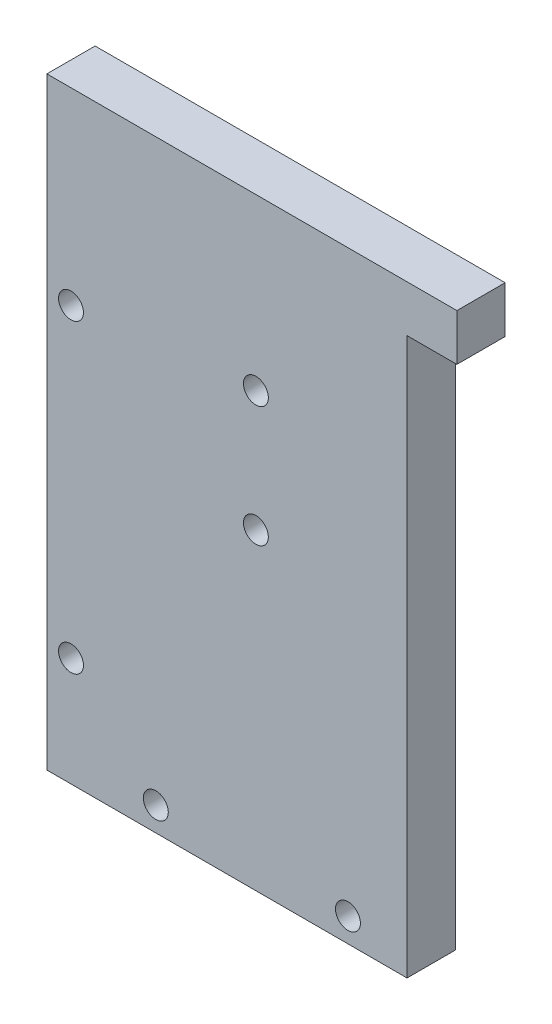
SolidWorks part; units mm, degrees
ref_plane "Płaszczyzna przednia" through (0, 0, 0) normal (0, 0, 1) x (1, 0, 0)
ref_plane "Płaszczyzna górna" through (0, 0, 0) normal (0, 1, 0) x (1, 0, 0)
ref_plane "Płaszczyzna prawa" through (0, 0, 0) normal (1, 0, 0) x (0, 0, -1)
sketch "Szkic1" plane through (0, 0, 0) normal (0, 0, 1) x (1, 0, 0)
  line L0 (4.4912, 6) -> (4.4912, 81)
  line L1 (4.4912, 6) -> (55.4912, 6)
  line L2 (4.4912, 81) -> (55.4912, 81)
  line L4 (55.4912, 81) -> (55.4912, 6)
  dimension "D1" = 75
extrude "Dodanie-wyciągnięcie1" add sketch "Szkic1" along normal blind 6
sketch "Szkic2" plane through (0, 0, 0) normal (0, 0, -1) x (-1, 0, 0)
  line L0 (-40.3912, 12) -> (-40.3912, 6) construction
  line L1 (-40.3912, 12) -> (-40.3912, 6)
  line L2 (-16.4912, 12) -> (-16.4912, 6) construction
  line L3 (-16.4912, 12) -> (-16.4912, 6)
  line L4 (-55.4912, 81) -> (-55.4912, 6)
  line L5 (-55.4912, 6) -> (-4.4912, 6)
  line L6 (-4.4912, 6) -> (-4.4912, 81)
  line L7 (-4.4912, 81) -> (-55.4912, 81)
  line L8 (-55.4912, 81) -> (-55.4912, 6)
  line L9 (-55.4912, 6) -> (-4.4912, 6)
  line L10 (-4.4912, 6) -> (-4.4912, 81)
  line L11 (-4.4912, 81) -> (-55.4912, 81)
  line L12 (-43.4912, 12) -> (-43.4912, 6) construction
  line L13 (-19.5912, 12) -> (-19.5912, 6) construction
  line L14 (-10.4912, 21.1) -> (-4.4912, 21.1) construction
  line L15 (-10.4912, 59.1) -> (-4.4912, 59.1) construction
  line L16 (-10.4912, 18) -> (-4.4912, 18) construction
  line L17 (-10.4912, 56) -> (-4.4912, 56) construction
  line L18 (-43.4912, 12) -> (-43.4912, 6)
  line L19 (-19.5912, 12) -> (-19.5912, 6)
  line L20 (-10.4912, 21.1) -> (-4.4912, 21.1)
  line L21 (-10.4912, 59.1) -> (-4.4912, 59.1)
  line L22 (-10.4912, 18) -> (-4.4912, 18)
  line L23 (-10.4912, 56) -> (-4.4912, 56)
  line L24 (-43.4912, 9) -> (-40.3912, 9)
  line L25 (-19.5912, 9) -> (-16.4912, 9)
  line L26 (-7.4912, 18) -> (-7.4912, 21.1)
  line L27 (-7.4912, 56) -> (-7.4912, 59.1)
  circle A0 centre (-18.0412, 9) radius 1.55
  circle A1 centre (-41.9412, 9) radius 1.55
  circle A2 centre (-7.4912, 19.55) radius 1.55
  circle A3 centre (-7.4912, 57.55) radius 1.55
  dimension "D2" = 3.1
  dimension "D3" = 3.1
  dimension "D4" = 3.1
  dimension "D5" = 3.1
  dimension "D1" = 0
sketch "Szkic3" plane through (0, 0, 0) normal (0, 0, -1) x (-1, 0, 0)
  circle A0 centre (-18.0412, 9) radius 1.55 construction
  circle A1 centre (-41.9412, 9) radius 1.55 construction
  circle A2 centre (-7.4912, 19.55) radius 1.55 construction
  circle A3 centre (-7.4912, 57.55) radius 1.55 construction
  circle A4 centre (-18.0412, 9) radius 1.55
  circle A5 centre (-41.9412, 9) radius 1.55
  circle A6 centre (-7.4912, 19.55) radius 1.55
  circle A7 centre (-7.4912, 57.55) radius 1.55
extrude "Wytnij-wyciągnięcie1" cut sketch "Szkic3" against normal through all
sketch "Szkic4" plane through (0, 0, 0) normal (0, 0, -1) x (-1, 0, 0)
  line L4 (-55.4912, 81) -> (-55.4912, 6)
  line L5 (-55.4912, 6) -> (-4.4912, 6)
  line L6 (-4.4912, 6) -> (-4.4912, 81)
  line L7 (-4.4912, 81) -> (-55.4912, 81)
  line L8 (-55.4912, 81) -> (-55.4912, 6)
  line L9 (-55.4912, 6) -> (-4.4912, 6)
  line L10 (-4.4912, 6) -> (-4.4912, 81)
  line L11 (-4.4912, 81) -> (-55.4912, 81)
  circle A0 centre (-30.4912, 44.872) radius 1.75 construction
  circle A1 centre (-30.4912, 44.872) radius 1.75
  circle A2 centre (-30.4912, 44.872) radius 1.55
  dimension "D1" = 3.1
  dimension "D2" = 0
sketch "Szkic5" plane through (0, 0, 0) normal (0, 0, -1) x (-1, 0, 0)
  circle A0 centre (-30.4912, 59.872) radius 1.55 construction
  circle A1 centre (-30.4912, 44.872) radius 1.55 construction
  circle A2 centre (-30.4912, 59.872) radius 1.55
  circle A3 centre (-30.4912, 44.872) radius 1.55
extrude "Wytnij-wyciągnięcie2" cut sketch "Szkic5" against normal blind 6
sketch "Szkic6" plane through (0, 0, 0) normal (0, 0, -1) x (-1, 0, 0)
  line L8 (-49.2912, 5.8) -> (-49.2912, 75.2)
  line L9 (-55.6912, 75.2) -> (-49.2912, 75.2)
  line L10 (-55.6912, 5.8) -> (-55.6912, 75.2)
  line L11 (-49.2912, 5.8) -> (-55.6912, 5.8)
extrude "Wytnij-wyciągnięcie3" cut sketch "Szkic6" against normal blind 10
equation "\"tolerancja_wpusy\"=0.2"
equation "\"dlugosc_wpustu_duzy\"=20"
equation "\"srednica_otworu_M3\"=3.1"
equation "\"szerokosc_nogi_T\"=3.1"
equation "\"dlugosc_T_30\"=11"
equation "\"grubosc_na_nakretke_kwadrat\"=2"
equation "\"szerokosc_na_nakretke_kwadrat\"=5.85"
equation "\"wyokosc_nadstawki_T\"=0.5"
equation "\"dlugosc_T_20_6\"=14"
equation "\"D2@Szkic2\"=\"srednica_otworu_M3\""
equation "\"D3@Szkic2\"=\"srednica_otworu_M3\""
equation "\"D4@Szkic2\"=\"srednica_otworu_M3\""
equation "\"D5@Szkic2\"=\"srednica_otworu_M3\""
